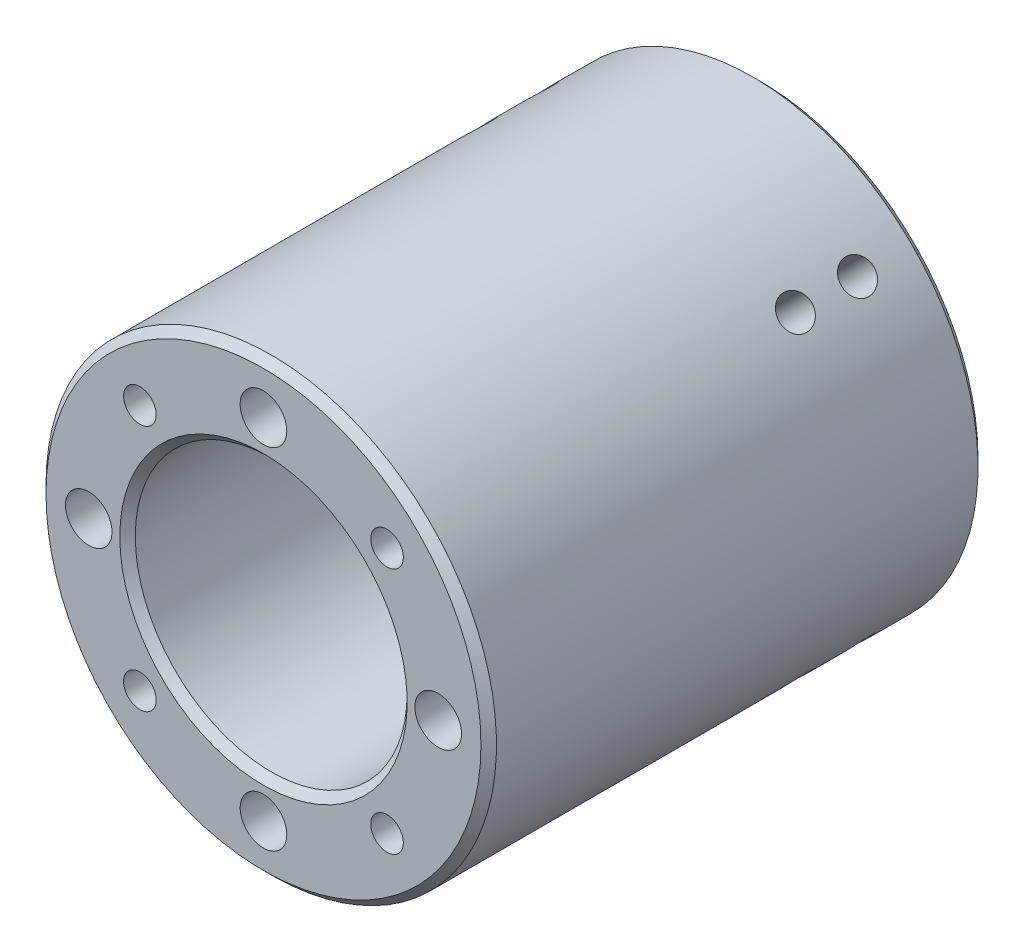
SolidWorks part; units mm, degrees
material "7050-T73510"
ref_plane "前视基准面" through (0, 0, 0) normal (0, 0, 1) x (1, 0, 0)
ref_plane "上视基准面" through (0, 0, 0) normal (0, 1, 0) x (1, 0, 0)
ref_plane "右视基准面" through (0, 0, 0) normal (1, 0, 0) x (0, 0, -1)
sketch "草图1" plane through (0, 0, 0) normal (1, 0, 0) x (0, 0, -1)
  line L0 (-74.6009, 0) -> (91.0329, 0) construction
  line L1 (0, 17.5) -> (40, 17.5)
  line L2 (40, 17.5) -> (40, 10)
  line L3 (40, 10) -> (64, 10)
  line L4 (0, 29) -> (64, 29)
  line L5 (0, 29) -> (0, 17.5)
  line L6 (64, 29) -> (64, 10)
  line L7 (0, 36.0374) -> (0, -10.1247) construction
  dimension "D1" = 35
  dimension "D2" = 40
  dimension "D3" = 20
  dimension "D4" = 58
  dimension "D5" = 24
  dimension "D6" = 64
revolve "旋转1" add sketch "草图1" angle 360 about L0
sketch "草图2" plane through (0, 0, 0) normal (0, 0, 1) x (1, 0, 0)
  line L0 (0, 31.2509) -> (0, -33.7203) construction
  line L1 (-39.5528, 0) -> (57.0461, 0) construction
  line L2 (-27.0864, 27.0864) -> (0, 0) construction
  line L3 (0, 0) -> (32.2866, -32.2866) construction
  circle A5 centre (22.5, 0) radius 3
  circle A6 centre (-22.5, 0) radius 3
  circle A7 centre (0, -22.5) radius 3
  circle A8 centre (0, 22.5) radius 3
  point P18 (-15.9099, 15.9099)
  point P20 (15.9099, 15.9099)
  point P22 (15.9099, -15.9099)
  point P23 (-15.9099, -15.9099)
  dimension "D2" = 22.5
  dimension "D3" = 6
  dimension "D1" = 45
sketch "草图3" plane through (0, 0, 0) normal (0, 0, 1) x (1, 0, 0)
  line L0 (-35.3405, 0) -> (40.481, 0) construction
  line L1 (0, 31.5728) -> (0, -36.7825) construction
  line L2 (0, 0) -> (15.9099, 15.9099) construction
  dimension "D1" = 22.5
  dimension "D2" = 45
hole_wizard "M5 螺纹孔1" positions "草图4" profile "草图5" tap size "M5" standard "GB"
sketch "草图4" plane through (0, 0, 0) normal (0, 0, 1) x (1, 0, 0)
  point P0 (15.9099, 15.9099)
cosmetic thread "装饰螺纹线1" parameters "D1"=10, "D2"=5
sketch "草图5" plane through (15.9099, 15.9099, 0) normal (1, 0, 0) x (0, -1, 0)
  line L0 (0, 0) -> (0, 15.2618)
  line L1 (0, 15.2618) -> (2.1, 14)
  line L2 (2.1, 14) -> (2.1, 0)
  line L5 (2.1, 0) -> (0, 0)
  line L10 (0, 15.2618) -> (-2.1, 14) construction
  line L11 (0, -6.35) -> (0, 107.95) construction
  dimension "螺纹孔钻头直径" = 4.2
  dimension "螺纹孔钻头深度" = 14
  dimension "导头角度" = 118
cosmetic thread "孔螺蚊线4" parameters "D1"=10, "D2"=5.2
pattern_circular "阵列(圆周)1" count 4 over 360 about axis through (0, 0, 0) along (0, 0, 1) of "M5 螺纹孔1"
cosmetic thread "装饰螺纹线4" parameters "D1"=5, "D2"=5
cosmetic thread "装饰螺纹线5" parameters "D1"=5, "D2"=5
cosmetic thread "装饰螺纹线6" parameters "D1"=5, "D2"=5
chamfer "倒角1" distance 1 angle 45 2 edges at (29, 0, -64) (29, 0, 0)
chamfer "倒角2" distance 1 angle 45 3 edges at (10, 0, -64) (17.5, 0, 0) (10, 0, -40)
ref_plane "基准面4" through (0, 0, 0) normal (0.7071, -0.7071, 0) x (0.7071, 0.7071, 0)
sketch "草图10" plane through (0, 0, 0) normal (0.7071, -0.7071, 0) x (0.7071, 0.7071, 0)
  line L0 (0, 17.4058) -> (0, -78.3963) construction
  line L1 (28, -64) -> (-28, -64) construction
  point P3 (0, -56)
  point P4 (0, -48)
  dimension "D1" = 8
  dimension "D2" = 8
hole_wizard "大小mm 暗销孔1" positions "草图15" profile "草图17" hole size "Ø6.0" standard "GB"
sketch "草图15" plane through (0, 0, 0) normal (0, 0, 1) x (1, 0, 0)
  point P0 (0, -22.5)
  point P3 (-22.5, 0)
  point P6 (0, 22.5)
  point P9 (22.5, 0)
sketch "草图17" plane through (0, -22.5, 0) normal (1, 0, 0) x (0, -1, 0)
  line L0 (0, 0) -> (0, 7.8026)
  line L1 (0, 7.8026) -> (3, 6)
  line L2 (3, 6) -> (3, 0)
  line L5 (3, 0) -> (0, 0)
  line L10 (0, 7.8026) -> (-3, 6) construction
  line L11 (0, -6.35) -> (0, 107.95) construction
  dimension "孔直径" = 6
  dimension "孔深度" = 6
  dimension "导头角度" = 118
hole_wizard "M5 螺纹孔2" positions "草图11" profile "草图12" tap size "M5" standard "GB"
sketch "草图11" plane through (0, 0, 0) normal (0.7071, -0.7071, 0) x (0.7071, 0.7071, 0)
  point P0 (0, -48)
  point P3 (0, -56)
cosmetic thread "装饰螺纹线2" parameters "D2"=5
cosmetic thread "装饰螺纹线3" parameters "D2"=5
sketch "草图12" plane through (0, 0, -48) normal (0.5774, 0.5774, 0.5774) x (-0.4082, -0.4082, 0.8165)
  line L0 (0, 0) -> (0, 41.0122)
  line L1 (0, 41.0122) -> (2.1, 41.0122)
  line L2 (2.1, 41.0122) -> (2.1, 0)
  line L5 (2.1, 0) -> (0, 0)
  line L11 (0, -6.35) -> (0, 107.95) construction
  dimension "通孔螺纹孔钻头直径" = 4.2
  dimension "通孔螺纹孔钻头深度" = 41.0122
cosmetic thread "孔螺蚊线2" parameters "D1"=10, "D2"=5.2
cosmetic thread "孔螺蚊线3" parameters "D1"=10, "D2"=5.2
pattern_circular "阵列(圆周)3" count 4 over 360 about axis through (0, 0, -63) along (0, 0, -1) of "M5 螺纹孔2"
